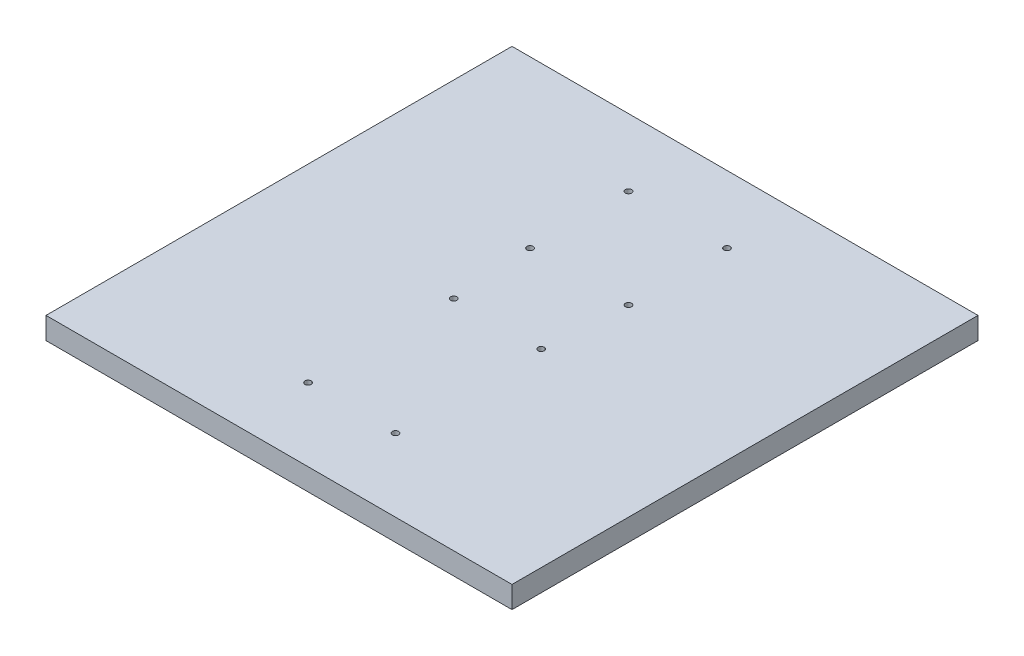
SolidWorks part; units mm, degrees
material "6061-T6 (SS)"
ref_plane "Front Plane" through (0, 0, 0) normal (0, 0, 1) x (1, 0, 0)
ref_plane "Top Plane" through (0, 0, 0) normal (0, 1, 0) x (1, 0, 0)
ref_plane "Right Plane" through (0, 0, 0) normal (1, 0, 0) x (0, 0, -1)
sketch "Sketch1" plane through (0, 0, 0) normal (0, 1, 0) x (1, 0, 0)
  line L1 (101.6, -101.6) -> (-101.6, -101.6)
  line L2 (101.6, -101.6) -> (101.6, 101.6)
  line L3 (101.6, 101.6) -> (-101.6, 101.6)
  line L4 (-101.6, -101.6) -> (-101.6, 101.6)
  line L5 (101.6, -101.6) -> (-101.6, 101.6) construction
  line L6 (101.6, 101.6) -> (-101.6, -101.6) construction
  point P0 (0, 0)
  dimension "D1" = 203.2
  dimension "D2" = 203.2
extrude "Boss-Extrude1" add sketch "Sketch1" along normal blind 9.525
hole_wizard "#6-32 Tapped Hole1" positions "Sketch3" profile "Sketch2" tap size "#6-32" standard "ANSI Inch" end condition up to next
sketch "Sketch3" plane through (0, 9.525, 0) normal (0, 1, 0) x (-1, 0, 0)
  line L0 (18.5463, -50.8) -> (0, -50.8) construction
  line L1 (0, -50.8) -> (0, 0) construction
  point P0 (21.463, -72.263)
  point P16 (-21.463, -72.263)
  point P17 (-21.463, -29.337)
  point P18 (21.463, -29.337)
  dimension "D1" = 50.8
  dimension "D2" = 42.926
  dimension "D3" = 42.926
sketch "Sketch2" plane through (-21.463, 9.525, -72.263) normal (1, 0, 0) x (0, 0, 1)
  line L0 (0, 0) -> (0, 9.525)
  line L1 (0, 9.525) -> (1.3525, 9.525)
  line L2 (1.3525, 9.525) -> (1.3525, 0)
  line L5 (1.3525, 0) -> (0, 0)
  line L11 (0, -6.35) -> (0, 107.95) construction
  dimension "Thread Major Dia." = 2.7051
  dimension "Thru Tap Drill Depth" = 9.525
hole_wizard "#6-32 Tapped Hole2" positions "Sketch4" profile "Sketch5" tap size "#6-32" standard "ANSI Inch" end condition up to next
sketch "Sketch4" plane through (0, 9.525, 0) normal (0, 1, 0) x (-1, 0, 0)
  line L2 (0, 0) -> (0, 38.1) construction
  line L3 (0, 38.1) -> (-26.5213, 38.1) construction
  point P20 (19.05, 6.35)
  point P31 (-19.05, 6.35)
  point P32 (-19.05, 69.85)
  point P33 (19.05, 69.85)
  dimension "D4" = 38.1
  dimension "D5" = 63.5
  dimension "D6" = 38.1
sketch "Sketch5" plane through (-19.05, 9.525, 6.35) normal (1, 0, 0) x (0, 0, 1)
  line L0 (0, 0) -> (0, 9.525)
  line L1 (0, 9.525) -> (1.3525, 9.525)
  line L2 (1.3525, 9.525) -> (1.3525, 0)
  line L5 (1.3525, 0) -> (0, 0)
  line L11 (0, -6.35) -> (0, 107.95) construction
  dimension "Thread Major Dia." = 2.7051
  dimension "Thru Tap Drill Depth" = 9.525
